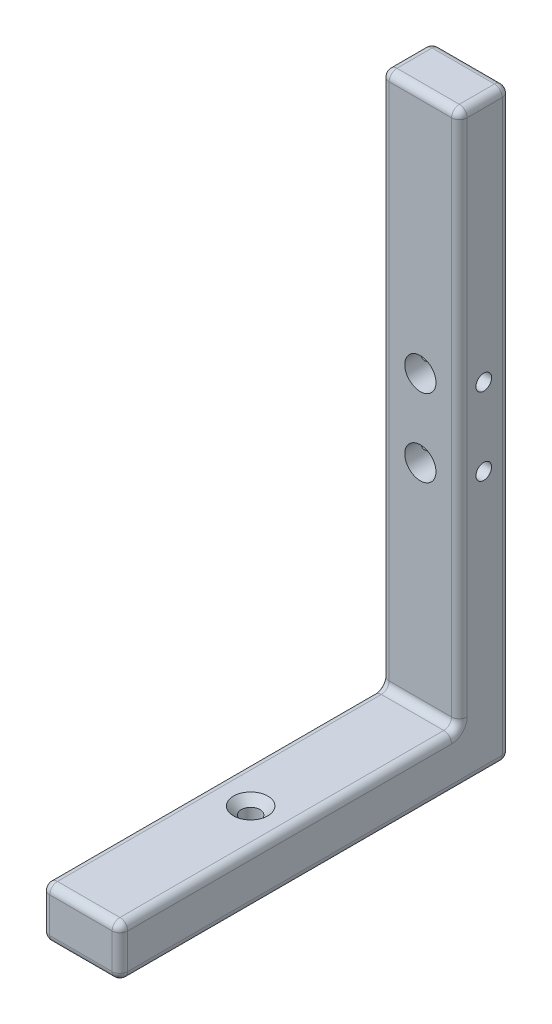
SolidWorks part; units mm, degrees
ref_plane "Front Plane" through (0, 0, 0) normal (0, 0, 1) x (1, 0, 0)
ref_plane "Top Plane" through (0, 0, 0) normal (0, 1, 0) x (1, 0, 0)
ref_plane "Right Plane" through (0, 0, 0) normal (1, 0, 0) x (0, 0, -1)
sketch "Sketch1" plane through (0, 0, 0) normal (1, 0, 0) x (0, 0, -1)
  line L0 (0, 0) -> (0, 75)
  line L1 (0, 75) -> (-6.5, 75)
  line L2 (-6.5, 75) -> (-6.5, 6.5)
  line L3 (-6.5, 6.5) -> (-50, 6.5)
  line L4 (-50, 6.5) -> (-50, 0)
  line L5 (-50, 0) -> (0, 0)
  dimension "D1" = 75
  dimension "D2" = 6.5
  dimension "D3" = 6.5
  dimension "D4" = 50
extrude "Boss-Extrude1" add sketch "Sketch1" along normal blind 10
sketch "Sketch2" plane through (0, 6.5, 0) normal (0, 1, 0) x (1, 0, 0)
  line L0 (5, -50) -> (5, -6.5) construction
  line L1 (10, -50) -> (0, -50) construction
  line L2 (10, -6.5) -> (0, -6.5) construction
  point P8 (5, -28.25)
hole_wizard "CSK for M2 Countersunk Flat Head Screw1" positions "Sketch2" profile "Sketch3" countersink size "M2" standard "ISO"
sketch "Sketch3" plane through (5, 6.5, 28.25) normal (1, 0, 0) x (0, 0, 1)
  line L0 (0, 0) -> (0, 30.721)
  line L1 (0, 30.721) -> (1.2, 30)
  line L2 (1.2, 30) -> (1.2, 1)
  line L3 (1.2, 1) -> (2.2, 0)
  line L5 (2.2, 0) -> (0, 0)
  line L6 (-1.2, 1) -> (-2.2, 0) construction
  line L10 (0, 30.721) -> (-1.2, 30) construction
  line L11 (0, -6.35) -> (0, 107.95) construction
  dimension "Hole Dia." = 2.4
  dimension "Hole Depth" = 30
  dimension "Near C'Sink Dia." = 4.4
  dimension "Near C'Sink Angle" = 90
  dimension "Drill Angle" = 118
sketch "Sketch4" plane through (0, 0, 0) normal (-1, 0, 0) x (0, 0, 1)
  line L0 (50, 0) -> (0, 0) construction
  circle A0 centre (3.371, 33.7) radius 1
  circle A1 centre (3.371, 43.6) radius 1
  dimension "D1" = 2
  dimension "D3" = 2
  dimension "D2" = 33.7
  dimension "D4" = 43.6
extrude "Cut-Extrude1" cut sketch "Sketch4" against normal through all
sketch "Sketch5" plane through (0, 0, 6.5) normal (0, 0, 1) x (1, 0, 0)
  line L0 (5, 6.5) -> (5, 75) construction
  line L1 (10, 6.5) -> (0, 6.5) construction
  line L2 (10, 75) -> (0, 75) construction
  circle A0 centre (5, 43.61) radius 2
  circle A1 centre (5, 33.71) radius 2
  dimension "D2" = 4
  dimension "D4" = 4
  dimension "D1" = 37.11
  dimension "D3" = 9.9
extrude "Cut-Extrude2" cut sketch "Sketch5" against normal through all
fillet "Fillet1" radius 1 18 edges at (5, 75, 0) (10, 75, 3.25) (5, 75, 6.5) (0, 75, 3.25) (5, 6.5, 50) (10, 3.25, 50) (5, 0, 50) (0, 3.25, 50) (0, 0, 25) (0, 37.5, 0) (5, 0, 0) (10, 37.5, 0) (10, 0, 25) (5, 6.5, 6.5) (0, 40.75, 6.5) (10, 40.75, 6.5) (0, 6.5, 28.25) (10, 6.5, 28.25)
